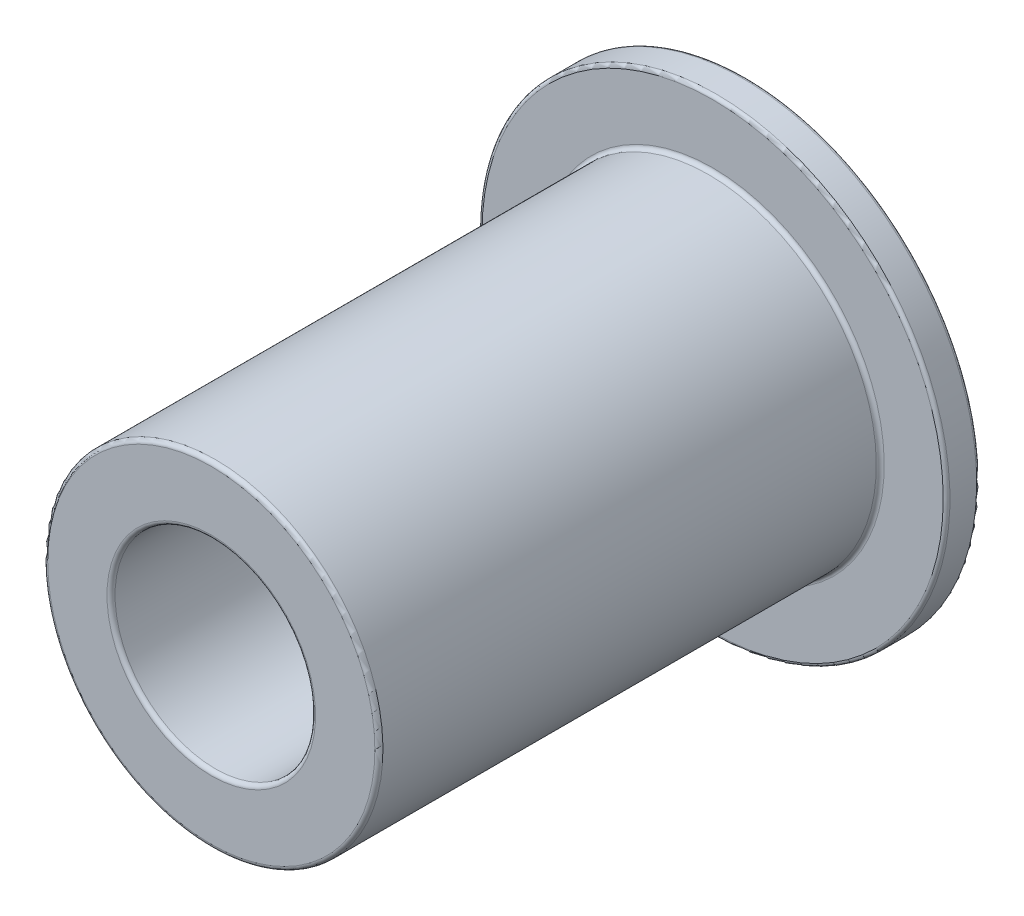
SolidWorks part; units mm, degrees
ref_plane "Front Plane" through (0, 0, 0) normal (0, 0, 1) x (1, 0, 0)
ref_plane "Top Plane" through (0, 0, 0) normal (0, 1, 0) x (1, 0, 0)
ref_plane "Right Plane" through (0, 0, 0) normal (1, 0, 0) x (0, 0, -1)
sketch "Sketch1" plane through (0, 0, 0) normal (1, 0, 0) x (0, 0, -1)
  line L0 (12.7, 0) -> (-12.7, 0) construction
  line L1 (-12.7, -4.7625) -> (-12.7, 4.7625)
  line L2 (12.7, -4.7625) -> (-12.7, -4.7625)
  line L3 (12.7, -4.7625) -> (12.7, 4.7625)
  line L4 (12.7, 4.7625) -> (-12.7, 4.7625)
  line L5 (-12.7, -4.7625) -> (-12.7, 4.7625)
  line L6 (12.7, -4.7625) -> (-12.7, 4.7625) construction
  line L7 (12.7, 4.7625) -> (-12.7, -4.7625) construction
  line L8 (11.1125, -11.1125) -> (12.7, -11.1125)
  line L9 (11.1125, -11.1125) -> (11.1125, 11.1125)
  line L10 (11.1125, 11.1125) -> (12.7, 11.1125)
  line L11 (12.7, -11.1125) -> (12.7, 11.1125)
  line L12 (11.1125, -11.1125) -> (12.7, 11.1125) construction
  line L13 (11.1125, 11.1125) -> (12.7, -11.1125) construction
  line L14 (-12.7, -7.9629) -> (11.1125, -7.9629)
  line L15 (-12.7, -7.9629) -> (-12.7, 7.9629)
  line L16 (-12.7, 7.9629) -> (11.1125, 7.9629)
  line L17 (11.1125, -7.9629) -> (11.1125, 7.9629)
  line L18 (-12.7, -7.9629) -> (11.1125, 7.9629) construction
  line L19 (-12.7, 7.9629) -> (11.1125, -7.9629) construction
  line L20 (-12.7, -7.9375) -> (-12.7, 7.9375)
  point P0 (0, 0)
  point P4 (0, 0)
  point P10 (11.9063, 0)
  point P15 (-0.7937, 0)
  point P23 (-12.7, 0)
  point P25 (-12.7, 0)
  point P26 (-12.7, -4.7625)
  point P27 (-12.7, 7.9375)
  dimension "ID" = 9.525
  dimension "Flange OD" = 22.225
  dimension "OD" = 15.9258
  dimension "Length" = 25.4
  dimension "Shaft Diameter" = 9.525
  dimension "Flange Thickness" = 1.5875
  dimension "For Shaft Diameter" = 9.525
  dimension "For Housing ID" = 15.875
sketch "Sketch2" plane through (0, 0, 0) normal (1, 0, 0) x (0, 0, -1)
  line L0 (-12.7, 0) -> (12.7, 0) construction
  line L1 (-12.7, 4.7625) -> (12.7, 4.7625)
  line L2 (12.7, 4.7625) -> (12.7, 11.1125)
  line L3 (12.7, 11.1125) -> (11.1125, 11.1125)
  line L4 (11.1125, 11.1125) -> (11.1125, 7.9629)
  line L5 (11.1125, 7.9629) -> (-12.7, 7.9629)
  line L6 (-12.7, 7.9629) -> (-12.7, 4.7625)
revolve "Revolve1" add sketch "Sketch2" angle 360 about L0
fillet "Fillet1" radius 0.1588 2 edges at (0, -11.1125, -12.7) (0, -11.1125, -11.1125)
fillet "Fillet2" radius 0.192 3 edges at (0, -4.7625, -12.7) (0, -7.9629, 12.7) (0, -4.7625, 12.7)
fillet "Fillet3" radius 0.189 1 edges at (0, -7.9629, -11.1125)
equation "\"D1@Fillet1\"=\"Flange Thickness@Sketch1\"*.1"
equation "\"D1@Fillet2\"=(\"OD@Sketch1\"-\"ID@Sketch1\")*.03"
equation "\"D1@Fillet3\"=(\"Flange OD@Sketch1\"-\"OD@Sketch1\")*.03"
